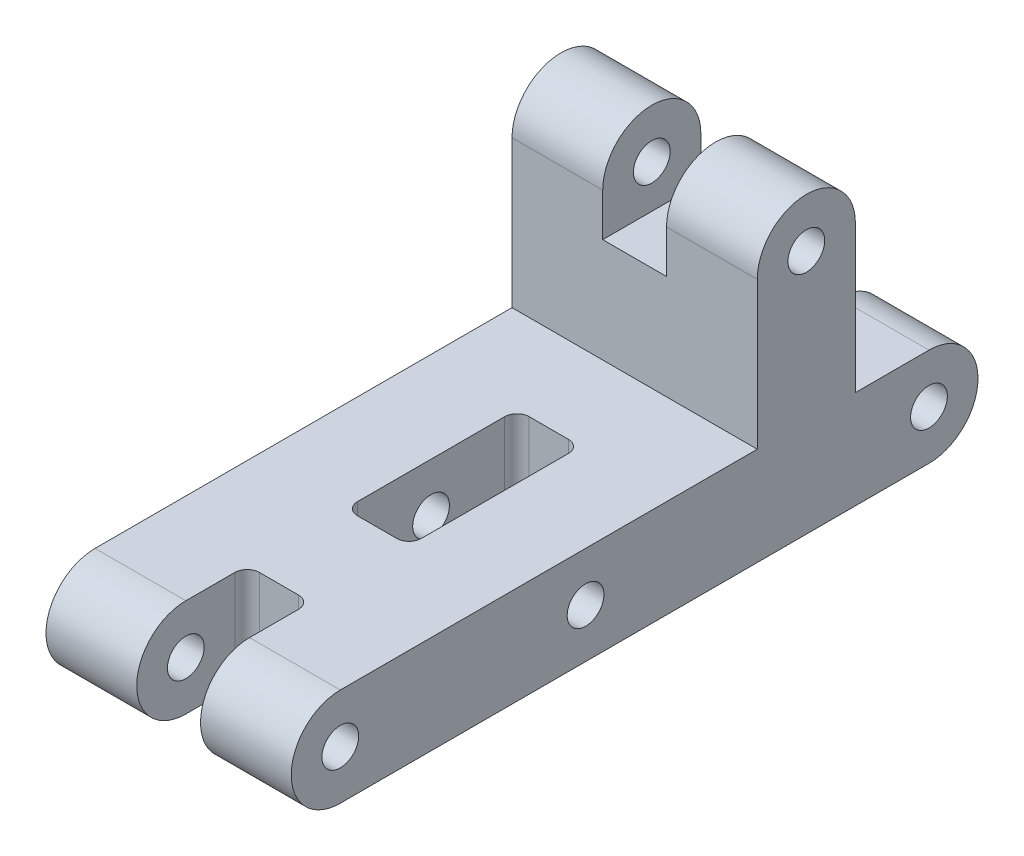
SolidWorks part; units mm, degrees
ref_plane "Alzado" through (0, 0, 0) normal (0, 0, 1) x (1, 0, 0)
ref_plane "Planta" through (0, 0, 0) normal (0, 1, 0) x (1, 0, 0)
ref_plane "Vista lateral" through (0, 0, 0) normal (1, 0, 0) x (0, 0, -1)
sketch "Croquis1" plane through (0, 0, 0) normal (1, 0, 0) x (0, 0, -1)
  line L0 (-14, 0) -> (14, 0) construction
  line L1 (-14, 4) -> (0, 4)
  line L2 (-14, -4) -> (14, -4)
  line L3 (8, 4) -> (14, 4)
  line L5 (0, 4) -> (0, 16)
  line L6 (0, 16) -> (8, 16) construction
  line L7 (8, 4) -> (8, 16)
  line L8 (-14, 4) -> (-34, 4)
  line L9 (-14, -4) -> (-34, -4)
  line L10 (-34, 4) -> (-34, -4) construction
  arc A0 (-14, 4) -> (-14, -4) centre (-14, 0) ccw construction
  arc A1 (14, -4) -> (14, 4) centre (14, 0) ccw
  circle A2 centre (14, 0) radius 1.5
  arc A3 (8, 16) -> (0, 16) centre (4, 16) ccw
  circle A4 centre (4, 16) radius 1.5
  circle A5 centre (-14, 0) radius 1.5
  arc A6 (-34, 4) -> (-34, -4) centre (-34, 0) ccw
  circle A7 centre (-34, 0) radius 1.5
  point P3 (0, 0)
  dimension "D2" = 4
  dimension "D3" = 3
  dimension "D4" = 4
  dimension "D7" = 20
  dimension "D1" = 28
  dimension "D5" = 6
  dimension "D6" = 12
extrude "Saliente-Extruir1" add sketch "Croquis1" along normal mid plane 20
sketch "Croquis2" plane through (0, 0, 0) normal (1, 0, 0) x (0, 0, -1)
  line L0 (0, 16) -> (0, 4) construction
  line L1 (0, 12.5) -> (8, 12.5)
  line L2 (0, 12.5) -> (0, 20)
  line L3 (0, 20) -> (8, 20)
  line L4 (8, 12.5) -> (8, 20)
  line L5 (8, 4) -> (8, 16) construction
  line L6 (0, 4) -> (-34, 4) construction
  line L7 (-7, 4) -> (-21, 4)
  line L8 (-7, 4) -> (-7, -4)
  line L9 (-7, -4) -> (-21, -4)
  line L10 (-21, 4) -> (-21, -4)
  line L11 (-34, -4) -> (14, -4) construction
  line L12 (14, 4) -> (8, 4) construction
  line L13 (9, 4) -> (18, 4)
  line L14 (9, 4) -> (9, -4)
  line L15 (9, -4) -> (18, -4)
  line L16 (18, 4) -> (18, -4)
  line L17 (0, 4) -> (-34, 4) construction
  line L18 (-29, 4) -> (-38, 4)
  line L19 (-29, 4) -> (-29, -4)
  line L20 (-29, -4) -> (-38, -4)
  line L21 (-38, 4) -> (-38, -4)
  line L22 (-34, -4) -> (14, -4) construction
  arc A0 (8, 16) -> (0, 16) centre (4, 16) ccw construction
  arc A2 (14, -4) -> (14, 4) centre (14, 0) ccw construction
  circle A4 centre (-14, 0) radius 1.5 construction
  arc A5 (-34, 4) -> (-34, -4) centre (-34, 0) ccw construction
  dimension "D5" = 9
  dimension "D1" = 7.5
  dimension "D2" = 7
  dimension "D3" = 9
  dimension "D4" = 7
extrude "Cortar-Extruir1" cut sketch "Croquis2" against normal mid plane 5.2
fillet "Redondeo1" radius 1 8 edges at (2.6, 0, 7) (2.6, 0, 21) (-2.6, 0, 7) (-2.6, 0, 21) (2.6, 0, 29) (-2.6, 0, 29) (2.6, 0, -9) (-2.6, 0, -9)
